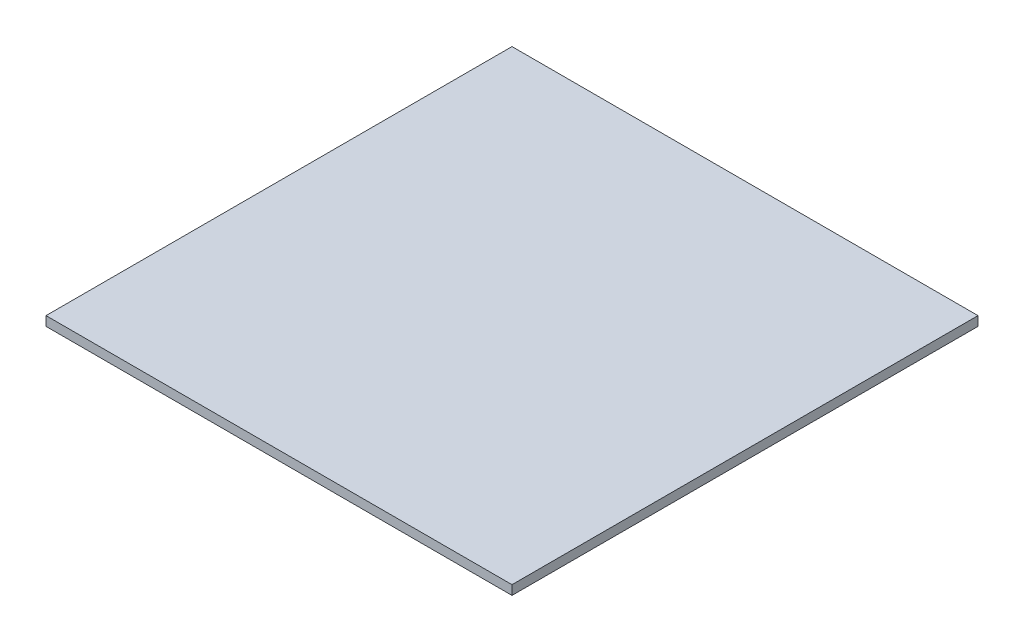
SolidWorks part; units mm, degrees
ref_plane "Front Plane" through (0, 0, 0) normal (0, 0, 1) x (1, 0, 0)
ref_plane "Top Plane" through (0, 0, 0) normal (0, 1, 0) x (1, 0, 0)
ref_plane "Right Plane" through (0, 0, 0) normal (1, 0, 0) x (0, 0, -1)
sketch "Sketch1" plane through (0, 0, 0) normal (0, 0, 1) x (1, 0, 0)
  line L1 (-237.7, -9.525) -> (237.7, -9.525)
  line L2 (-237.7, -9.525) -> (-237.7, 0)
  line L3 (-237.7, 0) -> (237.7, 0)
  line L4 (237.7, -9.525) -> (237.7, 0)
  line L5 (-237.7, -9.525) -> (237.7, 0) construction
  line L6 (-237.7, 0) -> (237.7, -9.525) construction
  point P0 (0, 0)
  dimension "D1" = 9.525
  dimension "D2" = 475.4
extrude "Extrude1" add sketch "Sketch1" against normal mid plane 475.4
